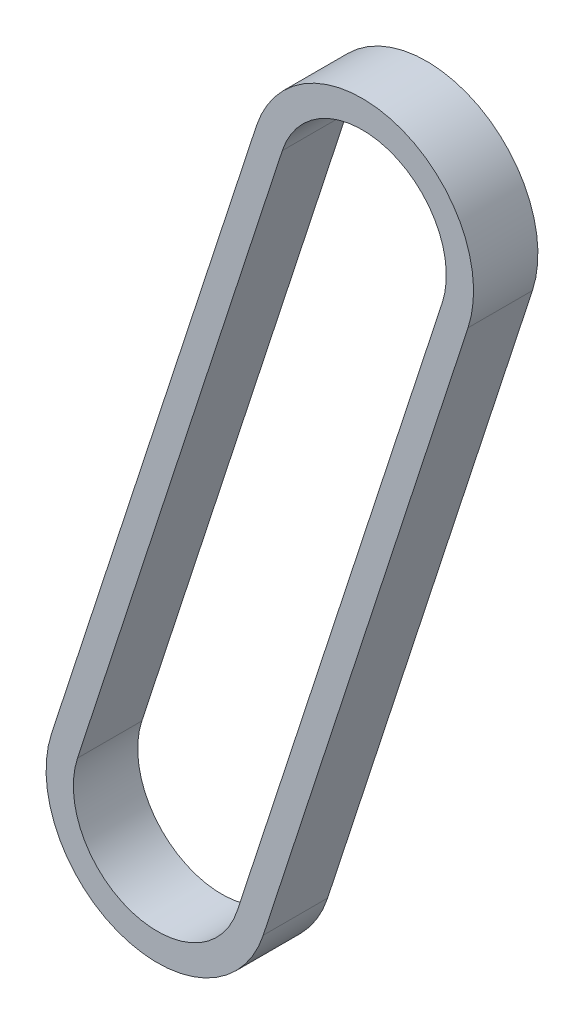
SolidWorks part; units mm, degrees
ref_plane "Front Plane" through (0, 0, 0) normal (0, 0, 1) x (1, 0, 0)
ref_plane "Top Plane" through (0, 0, 0) normal (0, 1, 0) x (1, 0, 0)
ref_plane "Right Plane" through (0, 0, 0) normal (1, 0, 0) x (0, 0, -1)
sketch "Sketch2" plane through (0, 0, 0) normal (0, 0, 1) x (1, 0, 0)
  line L0 (0, 0) -> (1, 0) construction
  line L1 (0, 0) -> (0, 1) construction
  line L2 (-13.1523, 4.2863) -> (15.4903, 92.1733)
  line L3 (41.7948, 83.6006) -> (13.1523, -4.2863)
  arc A0 (13.1523, -4.2863) -> (-13.1523, 4.2863) centre (0, 0) cw
  arc A1 (15.4903, 92.1733) -> (41.7948, 83.6006) centre (28.6425, 87.8869) cw
extrude "Extrude-Thin1" add sketch "Sketch2" along normal mid plane 9 thin thin type two direction wall 1.73 second wall 2.08
equation "\"D1@Extrude-Thin1\"=9mm"
equation "\"D5@Extrude-Thin1\"=1.73mm"
equation "\"D6@Extrude-Thin1\"=2.08mm"
